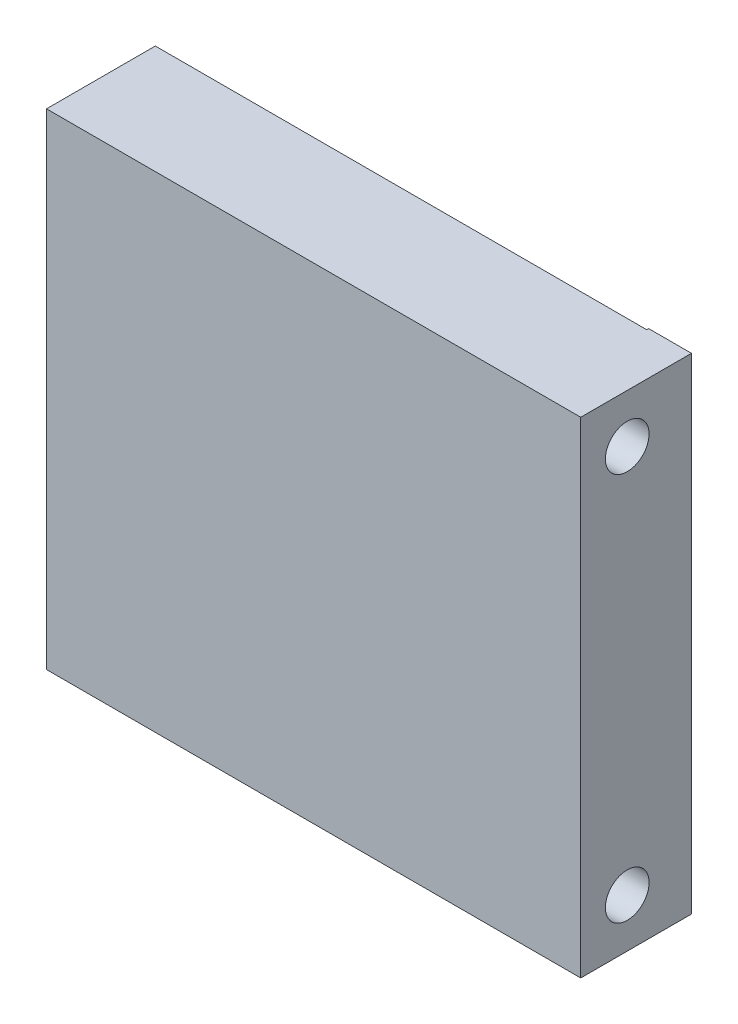
SolidWorks part; units mm, degrees
ref_plane "Front Plane" through (0, 0, 0) normal (1, 0, 0) x (0, 1, 0)
ref_plane "Top Plane" through (0, 0, 0) normal (0, 0, 1) x (0, 1, 0)
ref_plane "Right Plane" through (0, 0, 0) normal (0, 1, 0) x (-1, 0, 0)
sketch "Sketch1" plane through (0, 0, 0) normal (0, 0, 1) x (0, 1, 0)
  line L1 (-25, 25.3) -> (19, 25.3)
  line L2 (-25, 25.3) -> (-25, -25.3)
  line L3 (-25, -25.3) -> (25, -25.3)
  line L4 (25, 25.3) -> (25, -25.3)
  line L5 (-25, 25.3) -> (25, -25.3) construction
  line L6 (-25, -25.3) -> (25, 25.3) construction
  line L9 (19, 25.3) -> (25, 25.3)
  point P0 (0, 0)
  point P7 (18.5399, 25.3)
  dimension "D1" = 50
  dimension "D2" = 50.6
extrude "Boss-Extrude1" add sketch "Sketch1" along normal blind 1
sketch "Sketch2" plane through (25.3, 0, 0) normal (1, 0, 0) x (0, 1, 0)
  line L1 (25, 1) -> (-25, 1)
  line L2 (25, 1) -> (25, -10.4)
  line L3 (25, -10.4) -> (-25, -10.4)
  line L4 (-25, 1) -> (-25, -10.4)
  dimension "D1" = 11.4
extrude "Boss-Extrude2" add sketch "Sketch2" along normal blind 4.4
sketch "Sketch3" plane through (29.7, 0, 0) normal (1, 0, 0) x (0, 1, 0)
  line L0 (-20, -3.7871) -> (20, -3.7871) construction
  line L1 (-25, 1) -> (-25, -10.4) construction
  circle A0 centre (-20, -3.7871) radius 2.25
  circle A1 centre (20, -3.7871) radius 2.25
  dimension "D1" = 4.5
  dimension "D2" = 4.5
  dimension "D3" = 40
  dimension "D4" = 5
extrude "Cut-Extrude1" cut sketch "Sketch3" against normal blind 4.4
sketch "Sketch4" plane through (0, 0, 0) normal (0, 0, -1) x (1, 0, 0)
  line L0 (-25.3, -19.5) -> (-25.3, -25)
  line L1 (-25.3, 19.5) -> (25.3, 19.5)
  line L3 (-25.3, -19.5) -> (25.3, -19.5)
  line L7 (-25.3, 25) -> (25.3, 25)
  line L8 (-25.3, 25) -> (-25.3, 19.5)
  line L9 (-25.3, -25) -> (25.3, -25)
  line L10 (25.3, 25) -> (25.3, 19.5)
  line L11 (-25.3, 25) -> (-19.734, 19.5) construction
  line L12 (-25.3, -25) -> (-19.734, -19.5) construction
  line L13 (19.734, 19.5) -> (25.3, 25) construction
  line L14 (19.734, -19.5) -> (25.3, -25) construction
  line L15 (25.3, -19.5) -> (25.3, -25)
  point P0 (0, 0)
  point P6 (0, 0)
  dimension "D1" = 50.6
  dimension "D2" = 39
  dimension "D3" = 5.5
  dimension "D4" = 5.5
extrude "Boss-Extrude3" add sketch "Sketch4" along normal blind 6.4
sketch "Sketch5" plane through (0, 0, -6.4) normal (0, 0, -1) x (1, 0, 0)
  line L0 (-25.3, 20.5) -> (-25.3, 25)
  line L5 (25.3, -25) -> (-25.3, -25)
  line L6 (25.3, -20.5) -> (-25.3, -20.5)
  line L13 (25.3, 20.5) -> (-25.3, 20.5)
  line L18 (25.3, -25) -> (25.3, -20.5)
  line L19 (25.3, 25) -> (-25.3, 25)
  line L20 (-25.3, -25) -> (-25.3, -20.5)
  line L21 (25.3, -25) -> (20.746, -20.5) construction
  line L22 (25.3, 25) -> (20.746, 20.5) construction
  line L23 (-20.746, -20.5) -> (-25.3, -25) construction
  line L24 (-20.746, 20.5) -> (-25.3, 25) construction
  line L25 (25.3, 20.5) -> (25.3, 25)
  point P0 (0, 0)
  point P5 (0, 0)
  dimension "D1" = 41
  dimension "D2" = 50.6
extrude "Boss-Extrude4" add sketch "Sketch5" along normal blind 1.8
sketch "Sketch6" plane through (0, 0, -8.2) normal (0, 0, -1) x (1, 0, 0)
  line L0 (-25.3, -19.5) -> (-25.3, -25)
  line L5 (19.734, -19.5) -> (25.3, -25) construction
  line L23 (25.3, 19.5) -> (-25.3, 19.5)
  line L37 (25.3, -19.5) -> (-25.3, -19.5)
  line L41 (-25.3, 25) -> (25.3, 25)
  line L42 (-25.3, 25) -> (-25.3, 19.5)
  line L43 (-25.3, -25) -> (25.3, -25)
  line L44 (25.3, 25) -> (25.3, 19.5)
  line L46 (-25.3, -25) -> (-19.734, -19.5) construction
  line L47 (25.3, -19.5) -> (25.3, -25)
  point P0 (0, 0)
  point P6 (0, 0)
  dimension "D1" = 50.6
  dimension "D2" = 39
  dimension "D3" = 50.6
  dimension "D4" = 50
extrude "Boss-Extrude5" add sketch "Sketch6" along normal blind 2
